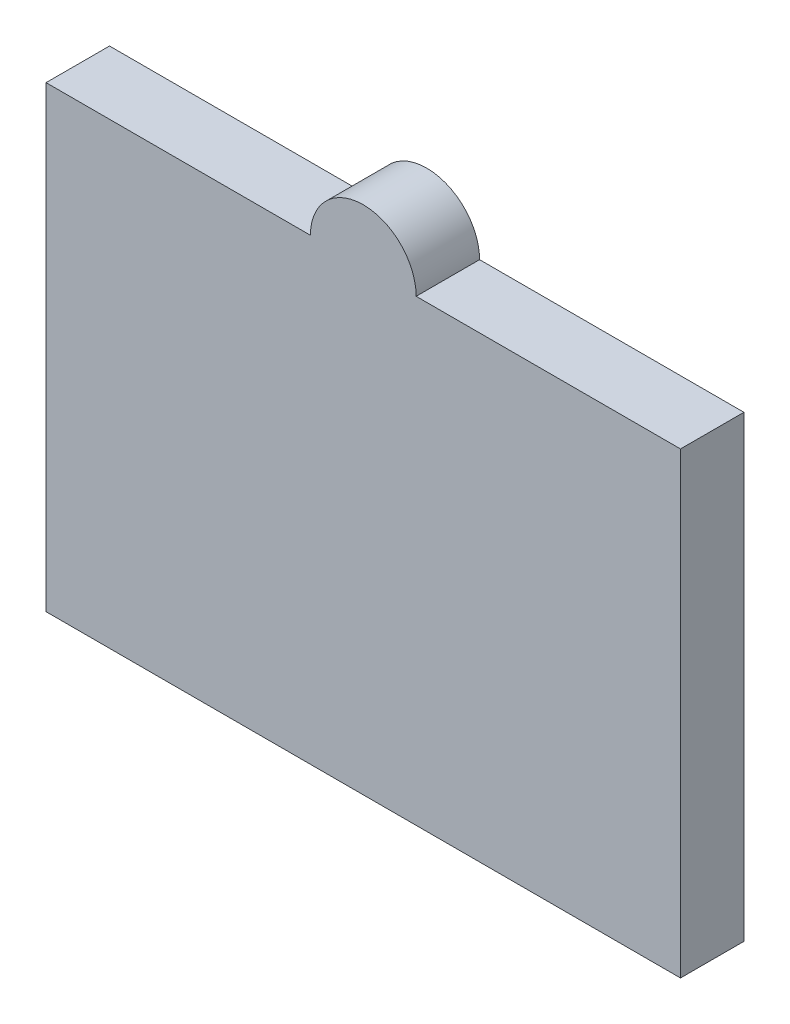
SolidWorks part; units mm, degrees
ref_plane "前基準面" through (0, 0, 0) normal (0, 0, 1) x (1, 0, 0)
ref_plane "上基準面" through (0, 0, 0) normal (0, 1, 0) x (1, 0, 0)
ref_plane "右基準面" through (0, 0, 0) normal (1, 0, 0) x (0, 0, -1)
sketch "草圖1" plane through (0, 0, 0) normal (0, 0, 1) x (1, 0, 0)
  line L0 (1.831, 5.8357) -> (9.331, 5.8357)
  line L1 (-8.669, 5.8357) -> (-1.169, 5.8357)
  line L2 (-8.669, 5.8357) -> (-8.669, -7.1643)
  line L3 (-8.669, -7.1643) -> (9.331, -7.1643)
  line L4 (9.331, 5.8357) -> (9.331, -7.1643)
  line L5 (9.331, 5.8357) -> (1.831, 5.8357) construction
  line L6 (-1.169, 5.8357) -> (-8.669, 5.8357) construction
  arc A1 (1.831, 5.8357) -> (-1.169, 5.8357) centre (0.331, 5.8357) ccw
  point P8 (0, 0)
  dimension "D3" = 3
  dimension "D1" = 18
  dimension "D2" = 13
extrude "填料-伸長1" add sketch "草圖1" along normal blind 1.8
sketch "草圖2" plane through (0, 0, 0) normal (0, 0, -1) x (-1, 0, 0)
  text T0 "MG996R" font "Century Gothic" height 3.5
extrude "填料-伸長2" add sketch "草圖2" along normal blind 0.1
sketch "草圖3" plane through (0, 0, 0) normal (0, 0, -1) x (-1, 0, 0)
  line L0 (-9.331, -7.1643) -> (-9.331, 5.8357) construction
  line L1 (-8.331, 4.8357) -> (7.669, 4.8357)
  line L2 (-8.331, 4.8357) -> (-8.331, -6.1643)
  line L3 (-8.331, -6.1643) -> (7.669, -6.1643)
  line L4 (7.669, 4.8357) -> (7.669, -6.1643)
  line L5 (-7.831, 4.3357) -> (7.169, 4.3357)
  line L6 (-7.831, 4.3357) -> (-7.831, -5.6643)
  line L7 (-7.831, -5.6643) -> (7.169, -5.6643)
  line L8 (7.169, 4.3357) -> (7.169, -5.6643)
  line L9 (8.669, 5.8357) -> (8.669, -7.1643) construction
  line L10 (8.669, -7.1643) -> (-9.331, -7.1643) construction
  line L11 (-9.331, 5.8357) -> (-1.831, 5.8357) construction
  dimension "D1" = 1
  dimension "D2" = 1
  dimension "D3" = 1
  dimension "D4" = 1
  dimension "D5" = 0.5
  dimension "D6" = 0.5
  dimension "D7" = 0.5
  dimension "D8" = 0.5
extrude "除料-伸長3" cut sketch "草圖3" against normal blind 0.1
fillet "圓角1" radius 0.04 4 edges at (-7.669, -0.6643, 0) (0.331, -6.1643, 0) (0.331, 4.8357, 0) (8.331, -0.6643, 0)
